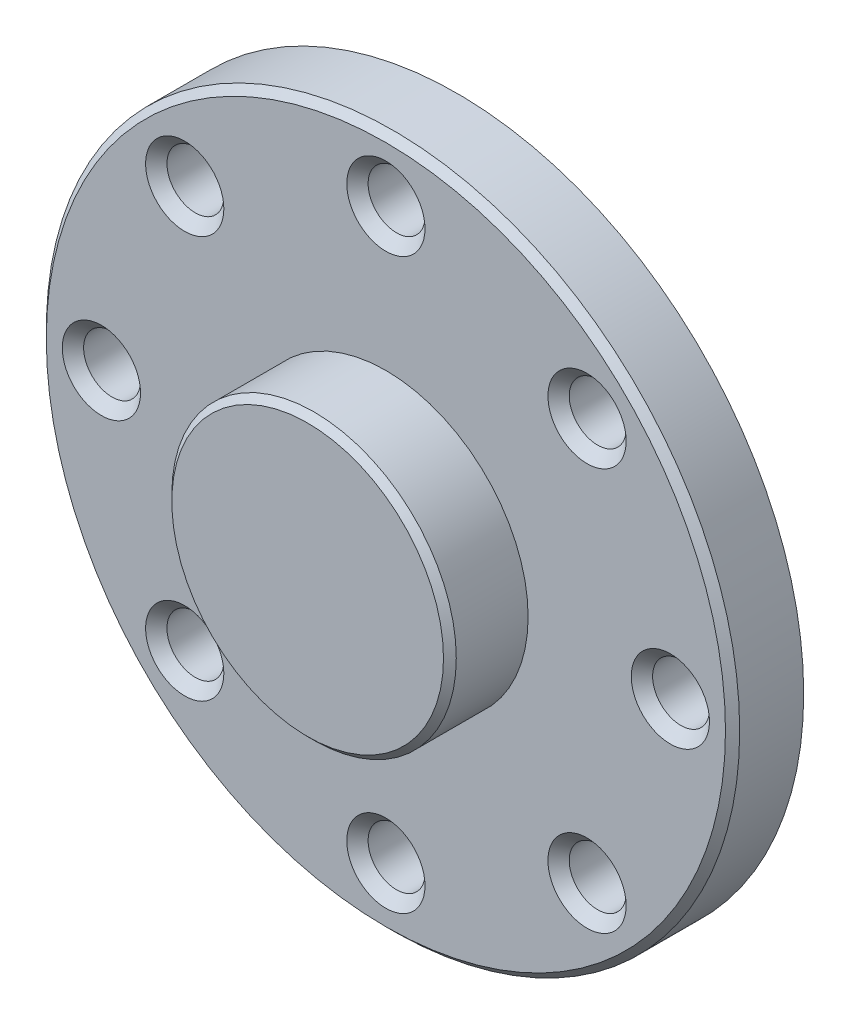
SolidWorks part; units mm, degrees
ref_plane "Front Plane" through (0, 0, 0) normal (0, 0, 1) x (1, 0, 0)
ref_plane "Top Plane" through (0, 0, 0) normal (0, 1, 0) x (1, 0, 0)
ref_plane "Right Plane" through (0, 0, 0) normal (1, 0, 0) x (0, 0, -1)
sketch "Sketch1" plane through (0, 0, 0) normal (0, 0, 1) x (1, 0, 0)
  circle A0 centre (0, 0) radius 9.75
  dimension "D1" = 19.5
extrude "Boss-Extrude1" add sketch "Sketch1" along normal blind 2
sketch "Sketch2" plane through (0, 0, 2) normal (0, 0, 1) x (1, 0, 0)
  circle A0 centre (0, 0) radius 4
  dimension "D1" = 8
extrude "Boss-Extrude2" add sketch "Sketch2" along normal blind 2.2
chamfer "Chamfer5" distance 0.2 angle 45 1 edges at (9.75, 0, 2)
chamfer "Chamfer6" distance 0.18 angle 45 1 edges at (4, 0, 4.2)
sketch "Sketch8" plane through (0, 0, 2) normal (0, 0, 1) x (1, 0, 0)
  circle A1 centre (0, 8) radius 0.8
  dimension "D2" = 1.6
extrude "Cut-Extrude1" cut sketch "Sketch8" against normal through all contours A1
chamfer "Chamfer7" distance 0.3 angle 45 1 edges at (0.8, 8, 2)
pattern_circular "CirPattern4" count 8 over 360 about axis through (0, 0, 0) along (0, 0, 1) of "Cut-Extrude1", "Chamfer7"
